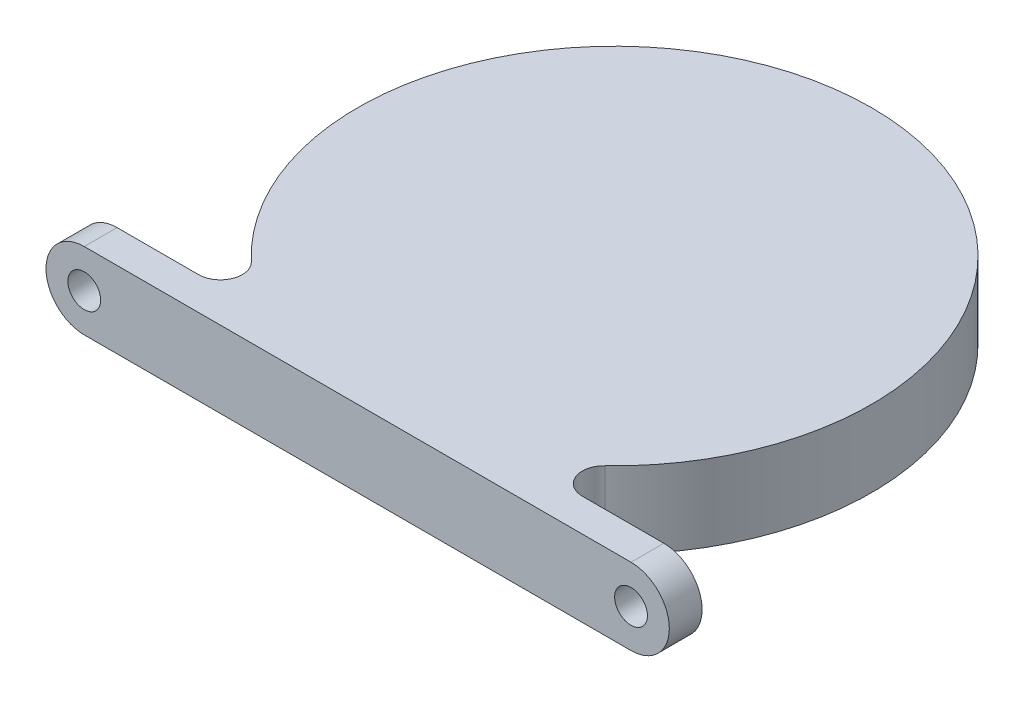
SolidWorks part; units mm, degrees
ref_plane "Front Plane" through (0, 0, 0) normal (0, 0, 1) x (1, 0, 0)
ref_plane "Top Plane" through (0, 0, 0) normal (0, 1, 0) x (1, 0, 0)
ref_plane "Right Plane" through (0, 0, 0) normal (1, 0, 0) x (0, 0, -1)
sketch "Sketch1" plane through (0, 0, 0) normal (0, 1, 0) x (1, 0, 0)
  circle A0 centre (0, 0) radius 23.5
  dimension "D1" = 47
extrude "Boss-Extrude1" add sketch "Sketch1" along normal blind 7
ref_plane "Plane1" through (0, 0, 23.5) normal (0, 0, 1) x (1, 0, 0)
sketch "Sketch2" plane through (0, 0, 23.5) normal (0, 0, 1) x (1, 0, 0)
  line L0 (23.5, 7) -> (-23.5, 0) construction
  line L1 (23.5, 0) -> (-23.5, 7) construction
  line L2 (25, 7) -> (25, 0) construction
  line L3 (-25, 0) -> (25, 0)
  line L5 (-25, 7) -> (25, 7)
  line L7 (-25, 0) -> (25, 7) construction
  line L8 (-25, 7) -> (25, 0) construction
  arc A0 (25, 0) -> (25, 7) centre (25, 3.5) ccw
  arc A1 (-25, 7) -> (-25, 0) centre (-25, 3.5) ccw
  circle A2 centre (25, 3.5) radius 1.5
  circle A3 centre (-25, 3.5) radius 1.5
  point P0 (23.5, 7)
  point P1 (23.5, 0)
  point P3 (-23.5, 7)
  point P5 (-23.5, 0)
  point P12 (0, 3.5)
  point P13 (0, 3.5)
  dimension "D3" = 3.5
  dimension "D4" = 3
  dimension "D1" = 7
  dimension "D2" = 50
extrude "Boss-Extrude2" add sketch "Sketch2" against normal blind 3
fillet "Fillet1" radius 2 2 edges at (-11.4891, 3.5, 20.5) (11.4891, 3.5, 20.5)
